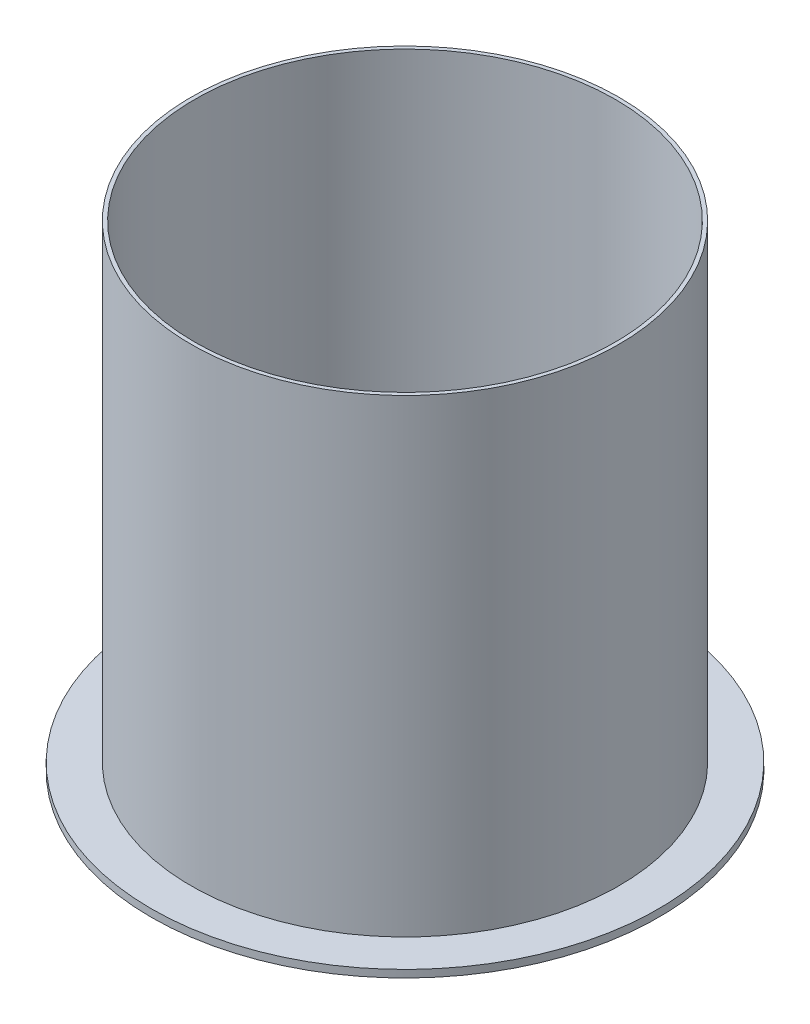
SolidWorks part; units mm, degrees
material "ASTM A36 Steel"
ref_plane "Front Plane" through (0, 0, 0) normal (0, 0, 1) x (1, 0, 0)
ref_plane "Top Plane" through (0, 0, 0) normal (0, 1, 0) x (1, 0, 0)
ref_plane "Right Plane" through (0, 0, 0) normal (1, 0, 0) x (0, 0, -1)
sketch "Sketch1" plane through (0, 0, 0) normal (0, 1, 0) x (1, 0, 0)
  circle A0 centre (0, 0) radius 1095.375
  circle A1 centre (0, 0) radius 1076.325
extrude "Boss-Extrude1" add sketch "Sketch1" along normal blind 2438.4
sketch "Sketch2" plane through (0, 0, 0) normal (0, 1, 0) x (1, 0, 0)
  circle A0 centre (0, 0) radius 1298.575
  circle A1 centre (0, 0) radius 1076.325
extrude "Boss-Extrude2" add sketch "Sketch2" along normal blind 38.1
